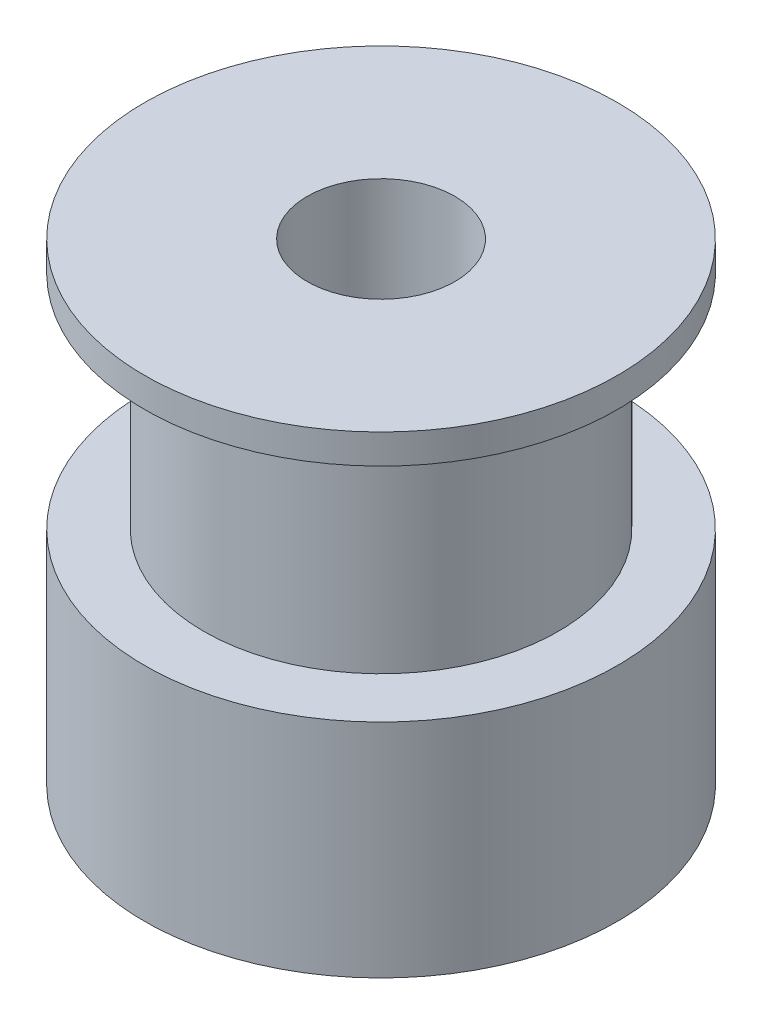
SolidWorks part; units mm, degrees
ref_plane "Front Plane" through (0, 0, 0) normal (0, 0, 1) x (1, 0, 0)
ref_plane "Top Plane" through (0, 0, 0) normal (0, 1, 0) x (1, 0, 0)
ref_plane "Right Plane" through (0, 0, 0) normal (1, 0, 0) x (0, 0, -1)
sketch "Sketch1" plane through (0, 0, 0) normal (0, 0, 1) x (1, 0, 0)
  line L0 (8, 0) -> (8, 7.5)
  line L1 (8, 7.5) -> (6, 7.5)
  line L2 (6, 7.5) -> (6, 15)
  line L3 (6, 15) -> (8, 15)
  line L4 (8, 15) -> (8, 16)
  line L5 (8, 16) -> (2.5, 16)
  line L6 (0, 0) -> (0, 16) construction
  line L7 (8, 0) -> (2.5, 0)
  line L8 (2.5, 16) -> (2.5, 0)
  dimension "D1" = 16
  dimension "D2" = 7.5
  dimension "D3" = 1
  dimension "D4" = 2.5
  dimension "D5" = 8
  dimension "D6" = 6
revolve "Revolve1" add sketch "Sketch1" angle 360 about L6
